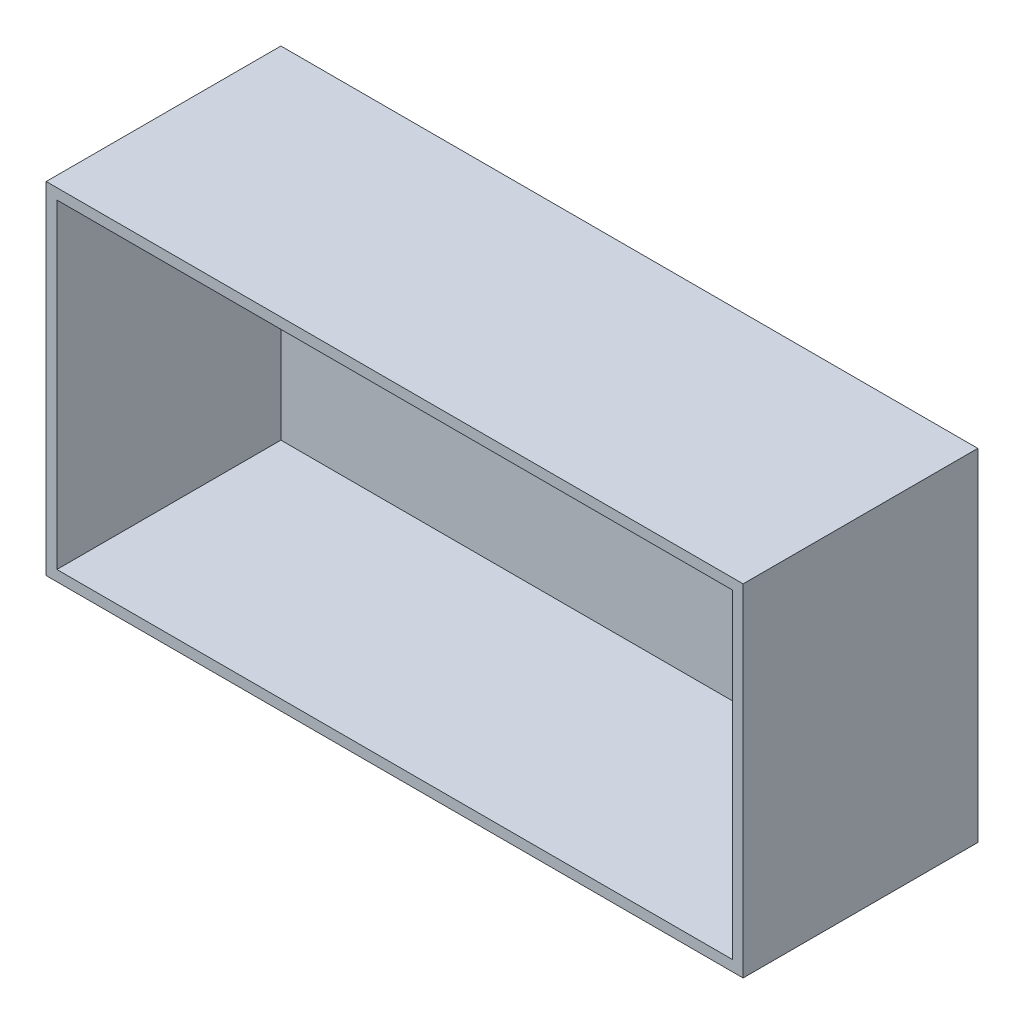
SolidWorks part; units mm, degrees
ref_plane "Front Plane" through (0, 0, 0) normal (0, 0, 1) x (1, 0, 0)
ref_plane "Top Plane" through (0, 0, 0) normal (0, 1, 0) x (1, 0, 0)
ref_plane "Right Plane" through (0, 0, 0) normal (1, 0, 0) x (0, 0, -1)
sketch "Sketch1" plane through (0, 0, 0) normal (0, 0, 1) x (1, 0, 0)
  line L1 (0, 0) -> (196, 0)
  line L2 (0, 0) -> (0, 96)
  line L3 (0, 96) -> (196, 96)
  line L4 (196, 0) -> (196, 96)
  line L5 (3, 3) -> (193, 3)
  line L6 (3, 3) -> (3, 93)
  line L7 (3, 93) -> (193, 93)
  line L8 (193, 3) -> (193, 93)
  dimension "D1" = 3
  dimension "D2" = 193
  dimension "D3" = 196
  dimension "D4" = 3
  dimension "D5" = 93
  dimension "D6" = 96
extrude "Profile" add sketch "Sketch1" along normal blind 66
sketch "Sketch2" plane through (0, 0, 0) normal (0, 0, 1) x (1, 0, 0)
  line L1 (3, 3) -> (193, 3)
  line L2 (3, 3) -> (3, 93)
  line L3 (3, 93) -> (193, 93)
  line L4 (193, 3) -> (193, 93)
extrude "Back" add sketch "Sketch2" along normal blind 3
equation "\"Profile_Depth\" = 66mm"
equation "\"D1@Profile\" = \"Profile_Depth\""
equation "\"Profile_Sketch_1\" = 3mm"
equation "\"D1@Sketch1\" = \"Profile_Sketch_1\""
equation "\"Profile_Sketch_2\" = 193mm"
equation "\"D2@Sketch1\" = \"Profile_Sketch_2\""
equation "\"Profile_Sketch_3\" = 196mm"
equation "\"D3@Sketch1\" = \"Profile_Sketch_3\""
equation "\"Profile_Sketch_4\" = 3mm"
equation "\"D4@Sketch1\" = \"Profile_Sketch_4\""
equation "\"Profile_Sketch_5\" = 93mm"
equation "\"D5@Sketch1\" = \"Profile_Sketch_5\""
equation "\"Profile_Sketch_6\" = 96mm"
equation "\"D6@Sketch1\" = \"Profile_Sketch_6\""
equation "\"Back_Depth\" = 3mm"
equation "\"D1@Back\" = \"Back_Depth\""
equation "\"EnvelopeWidth\" = 196mm"
equation "\"EnvelopeHeight\" = 96mm"
